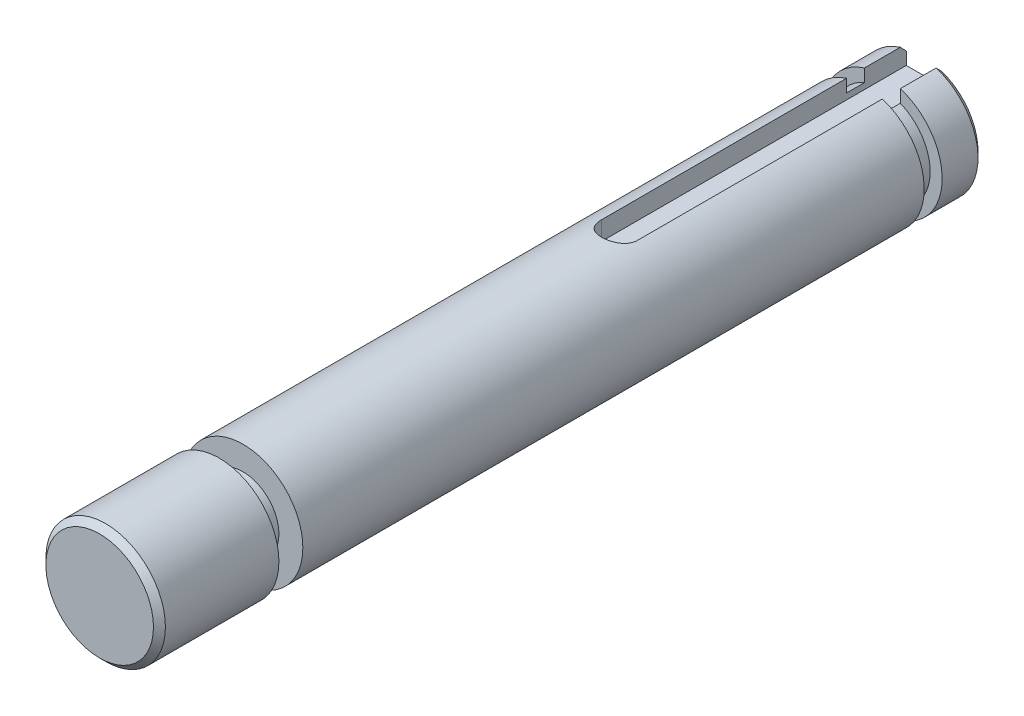
SolidWorks part; units mm, degrees
ref_plane "Front Plane" through (0, 0, 0) normal (0, 0, 1) x (1, 0, 0)
ref_plane "Top Plane" through (0, 0, 0) normal (0, 1, 0) x (1, 0, 0)
ref_plane "Right Plane" through (0, 0, 0) normal (1, 0, 0) x (0, 0, -1)
sketch "Sketch1" plane through (0, 0, 0) normal (0, 0, 1) x (1, 0, 0)
  circle A0 centre (0, 0) radius 5
  dimension "D1" = 10
extrude "Boss-Extrude1" add sketch "Sketch1" along normal mid plane 69
cosmetic thread "Cosmetic Thread1" parameters "D1"=7, "D2"=6.619
sketch "Sketch2" plane through (0, 0, 34.5) normal (0, 0, 1) x (1, 0, 0)
  circle A0 centre (0, 0) radius 3
  circle A1 centre (0, 0) radius 5
  circle A2 centre (0, 0) radius 5
  dimension "D2" = 6
  dimension "D1" = 0
extrude "Cut-Extrude1" cut sketch "Sketch2" against normal blind 2 from offset 10 offset against normal yes
sketch "Sketch3" plane through (0, 0, -34.5) normal (0, 0, -1) x (-1, 0, 0)
  circle A0 centre (0, 0) radius 4
  circle A1 centre (0, 0) radius 5
  dimension "D1" = 8
extrude "Cut-Extrude3" cut sketch "Sketch3" along normal blind 1.5 from offset 5 offset against normal yes
chamfer "Chamfer1" distance 0.5 angle 45 2 edges at (5, 0, -34.5) (5, 0, 34.5)
sketch "Sketch4" plane through (0, 0, 0) normal (0, 1, 0) x (1, 0, 0)
  line L0 (0, 34.5) -> (0, 9) construction
  line L1 (4.5, 34.5) -> (-4.5, 34.5) construction
  line L2 (1.5, 34.5) -> (1.5, 9)
  line L3 (-1.5, 34.5) -> (-1.5, 9)
  line L4 (-1.5, 34.5) -> (1.5, 34.5)
  arc A1 (-1.5, 9) -> (1.5, 9) centre (0, 9) ccw
  point P5 (0, 21.75)
  dimension "D2" = 1.5
  dimension "D1" = 25.5
extrude "Cut-Extrude4" cut sketch "Sketch4" along normal through all from offset 3.2
